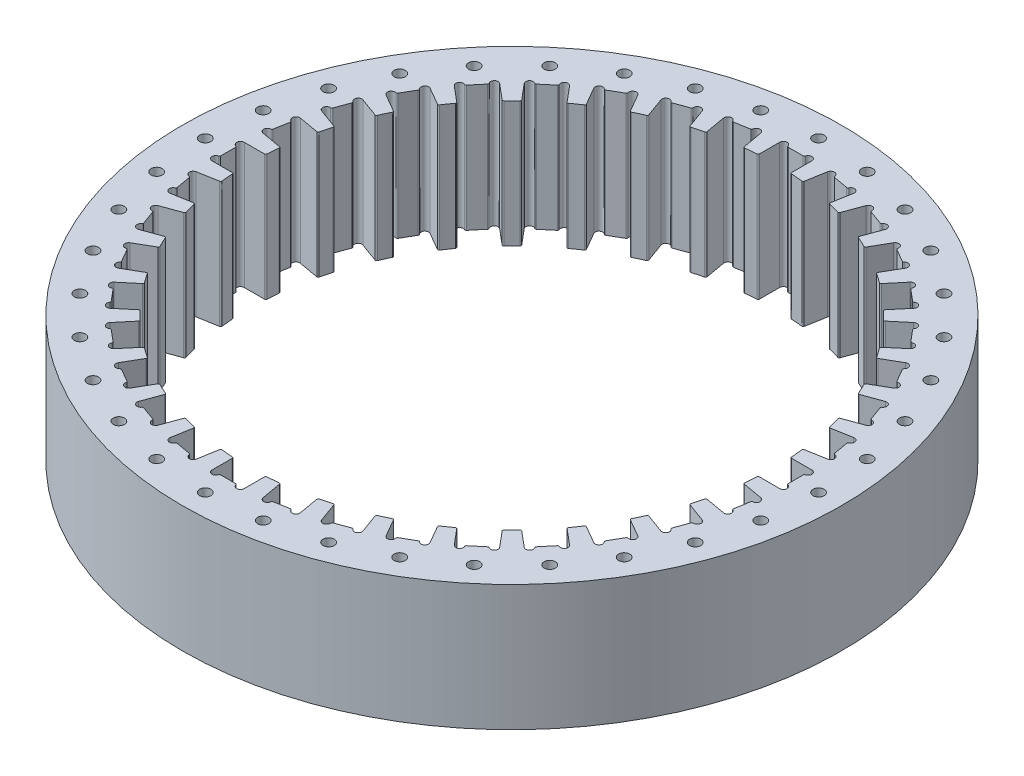
SolidWorks part; units mm, degrees
material "ABS"
ref_plane "Front Plane" through (0, 0, 0) normal (0, 0, 1) x (1, 0, 0)
ref_plane "Top Plane" through (0, 0, 0) normal (0, 1, 0) x (1, 0, 0)
ref_plane "Right Plane" through (0, 0, 0) normal (1, 0, 0) x (0, 0, -1)
sketch "Sketch1" plane through (0, 0, 0) normal (0, 1, 0) x (1, 0, 0)
  line L0 (12.4442, 51.8515) -> (13.1523, 55.8673)
  line L1 (11.433, 56.1704) -> (8.4679, 56.6933)
  line L2 (6.7487, 56.9964) -> (6.0406, 52.9807)
  line L3 (21.259, 48.9029) -> (22.6537, 52.7347)
  line L4 (21.0132, 53.3317) -> (18.1839, 54.3615)
  line L5 (16.5434, 54.9586) -> (15.1488, 51.1268)
  line L6 (29.428, 44.4683) -> (31.4668, 47.9997)
  line L7 (3.2512, 53.2247) -> (3.2512, 57.3024)
  line L8 (1.5055, 57.3024) -> (-1.5055, 57.3024)
  line L9 (-3.2512, 57.3024) -> (-3.2512, 53.2247)
  line L10 (29.955, 48.8726) -> (27.3474, 50.3781)
  line L11 (25.8356, 51.2509) -> (23.7967, 47.7195)
  line L12 (36.7027, 38.6827) -> (39.3238, 41.8064)
  line L13 (37.9865, 42.9285) -> (35.68, 44.8639)
  line L14 (34.3427, 45.986) -> (31.7216, 42.8623)
  line L15 (42.8623, 31.7216) -> (45.986, 34.3427)
  line L16 (44.8639, 35.68) -> (42.9285, 37.9865)
  line L17 (41.8064, 39.3238) -> (38.6827, 36.7027)
  line L18 (47.7195, 23.7967) -> (51.2509, 25.8356)
  line L19 (50.3781, 27.3474) -> (48.8726, 29.955)
  line L20 (47.9997, 31.4668) -> (44.4683, 29.428)
  line L21 (51.1268, 15.1488) -> (54.9586, 16.5434)
  line L22 (54.3615, 18.1839) -> (53.3317, 21.0132)
  line L23 (52.7347, 22.6537) -> (48.9029, 21.259)
  line L24 (52.9807, 6.0406) -> (56.9964, 6.7487)
  line L25 (56.6933, 8.4679) -> (56.1704, 11.433)
  line L26 (55.8673, 13.1523) -> (51.8515, 12.4442)
  line L27 (53.2247, -3.2512) -> (57.3024, -3.2512)
  line L28 (57.3024, -1.5055) -> (57.3024, 1.5055)
  line L29 (57.3024, 3.2512) -> (53.2247, 3.2512)
  line L30 (51.8515, -12.4442) -> (55.8673, -13.1523)
  line L31 (56.1704, -11.433) -> (56.6933, -8.4679)
  line L32 (56.9964, -6.7487) -> (52.9807, -6.0406)
  line L33 (48.9029, -21.259) -> (52.7347, -22.6537)
  line L34 (53.3317, -21.0132) -> (54.3615, -18.1839)
  line L35 (54.9586, -16.5434) -> (51.1268, -15.1488)
  line L36 (44.4683, -29.428) -> (47.9997, -31.4668)
  line L37 (48.8726, -29.955) -> (50.3781, -27.3474)
  line L38 (51.2509, -25.8356) -> (47.7195, -23.7967)
  line L39 (38.6827, -36.7027) -> (41.8064, -39.3238)
  line L40 (42.9285, -37.9865) -> (44.8639, -35.68)
  line L41 (45.986, -34.3427) -> (42.8623, -31.7216)
  line L42 (31.7216, -42.8623) -> (34.3427, -45.986)
  line L43 (35.68, -44.8639) -> (37.9865, -42.9285)
  line L44 (39.3238, -41.8064) -> (36.7027, -38.6827)
  line L45 (23.7967, -47.7195) -> (25.8356, -51.2509)
  line L46 (27.3474, -50.3781) -> (29.955, -48.8726)
  line L47 (31.4668, -47.9997) -> (29.428, -44.4683)
  line L48 (15.1488, -51.1268) -> (16.5434, -54.9586)
  line L49 (18.1839, -54.3615) -> (21.0132, -53.3317)
  line L50 (22.6537, -52.7347) -> (21.259, -48.9029)
  line L51 (6.0406, -52.9807) -> (6.7487, -56.9964)
  line L52 (8.4679, -56.6933) -> (11.433, -56.1704)
  line L53 (13.1523, -55.8673) -> (12.4442, -51.8515)
  line L54 (-3.2512, -53.2247) -> (-3.2512, -57.3024)
  line L55 (-1.5055, -57.3024) -> (1.5055, -57.3024)
  line L56 (3.2512, -57.3024) -> (3.2512, -53.2247)
  line L57 (-12.4442, -51.8515) -> (-13.1523, -55.8673)
  line L58 (-11.433, -56.1704) -> (-8.4679, -56.6933)
  line L59 (-6.7487, -56.9964) -> (-6.0406, -52.9807)
  line L60 (-21.259, -48.9029) -> (-22.6537, -52.7347)
  line L61 (-21.0132, -53.3317) -> (-18.1839, -54.3615)
  line L62 (-16.5434, -54.9586) -> (-15.1488, -51.1268)
  line L63 (-29.428, -44.4683) -> (-31.4668, -47.9997)
  line L64 (-29.955, -48.8726) -> (-27.3474, -50.3781)
  line L65 (-25.8356, -51.2509) -> (-23.7967, -47.7195)
  line L66 (-36.7027, -38.6827) -> (-39.3238, -41.8064)
  line L67 (-37.9865, -42.9285) -> (-35.68, -44.8639)
  line L68 (-34.3427, -45.986) -> (-31.7216, -42.8623)
  line L69 (-42.8623, -31.7216) -> (-45.986, -34.3427)
  line L70 (-44.8639, -35.68) -> (-42.9285, -37.9865)
  line L71 (-41.8064, -39.3238) -> (-38.6827, -36.7027)
  line L72 (-47.7195, -23.7967) -> (-51.2509, -25.8356)
  line L73 (-50.3781, -27.3474) -> (-48.8726, -29.955)
  line L74 (-47.9997, -31.4668) -> (-44.4683, -29.428)
  line L75 (-51.1268, -15.1488) -> (-54.9586, -16.5434)
  line L76 (-54.3615, -18.1839) -> (-53.3317, -21.0132)
  line L77 (-52.7347, -22.6537) -> (-48.9029, -21.259)
  line L78 (-52.9807, -6.0406) -> (-56.9964, -6.7487)
  line L79 (-56.6933, -8.4679) -> (-56.1704, -11.433)
  line L80 (-55.8673, -13.1523) -> (-51.8515, -12.4442)
  line L81 (-53.2247, 3.2512) -> (-57.3024, 3.2512)
  line L82 (-57.3024, 1.5055) -> (-57.3024, -1.5055)
  line L83 (-57.3024, -3.2512) -> (-53.2247, -3.2512)
  line L84 (-51.8515, 12.4442) -> (-55.8673, 13.1523)
  line L85 (-56.1704, 11.433) -> (-56.6933, 8.4679)
  line L86 (-56.9964, 6.7487) -> (-52.9807, 6.0406)
  line L87 (-48.9029, 21.259) -> (-52.7347, 22.6537)
  line L88 (-53.3317, 21.0132) -> (-54.3615, 18.1839)
  line L89 (-54.9586, 16.5434) -> (-51.1268, 15.1488)
  line L90 (-44.4683, 29.428) -> (-47.9997, 31.4668)
  line L91 (-48.8726, 29.955) -> (-50.3781, 27.3474)
  line L92 (-51.2509, 25.8356) -> (-47.7195, 23.7967)
  line L93 (-38.6827, 36.7027) -> (-41.8064, 39.3238)
  line L94 (-42.9285, 37.9865) -> (-44.8639, 35.68)
  line L95 (-45.986, 34.3427) -> (-42.8623, 31.7216)
  line L96 (-31.7216, 42.8623) -> (-34.3427, 45.986)
  line L97 (-35.68, 44.8639) -> (-37.9865, 42.9285)
  line L98 (-39.3238, 41.8064) -> (-36.7027, 38.6827)
  line L99 (-23.7967, 47.7195) -> (-25.8356, 51.2509)
  line L100 (-27.3474, 50.3781) -> (-29.955, 48.8726)
  line L101 (-31.4668, 47.9997) -> (-29.428, 44.4683)
  line L102 (-15.1488, 51.1268) -> (-16.5434, 54.9586)
  line L103 (-18.1839, 54.3615) -> (-21.0132, 53.3317)
  line L104 (-22.6537, 52.7347) -> (-21.259, 48.9029)
  line L105 (-6.0406, 52.9807) -> (-6.7487, 56.9964)
  line L106 (-8.4679, 56.6933) -> (-11.433, 56.1704)
  line L107 (-13.1523, 55.8673) -> (-12.4442, 51.8515)
  line L108 (0, 0) -> (50000, 0) construction
  line L109 (0, 0) -> (0, -50000) construction
  arc A0 (-3.4885, 52.9713) -> (-5.7629, 52.7723) centre (0, 0) ccw
  arc A1 (-1.5055, 57.3024) -> (-1.7514, 57.4929) centre (-1.5055, 57.5564) cw
  arc A2 (-1.7514, 57.4929) -> (-3.2512, 57.3024) centre (-2.4892, 57.3024) ccw
  arc A3 (1.7514, 57.4929) -> (3.2512, 57.3024) centre (2.4892, 57.3024) cw
  arc A4 (1.5055, 57.3024) -> (1.7514, 57.4929) centre (1.5055, 57.5564) ccw
  arc A5 (5.7629, 52.7723) -> (3.4885, 52.9713) centre (0, 0) ccw
  arc A6 (3.4885, 52.9713) -> (3.2512, 53.2247) centre (3.5052, 53.2247) cw
  arc A7 (-3.4885, 52.9713) -> (-3.2512, 53.2247) centre (-3.5052, 53.2247) ccw
  arc A8 (8.4679, 56.6933) -> (8.2587, 56.9236) centre (8.512, 56.9434) cw
  arc A9 (8.2587, 56.9236) -> (6.7487, 56.9964) centre (7.4991, 56.8641) ccw
  arc A10 (11.7083, 56.3153) -> (13.1523, 55.8673) centre (12.4018, 55.9996) cw
  arc A11 (11.433, 56.1704) -> (11.7083, 56.3153) centre (11.4772, 56.4206) ccw
  arc A12 (12.6339, 51.5607) -> (12.4442, 51.8515) centre (12.6943, 51.8074) cw
  arc A13 (5.7629, 52.7723) -> (6.0406, 52.9807) centre (5.7904, 53.0248) ccw
  arc A14 (14.8391, 50.9698) -> (12.6339, 51.5607) centre (0, 0) ccw
  arc A15 (18.1839, 54.3615) -> (18.018, 54.6247) centre (18.2708, 54.6002) cw
  arc A16 (18.018, 54.6247) -> (16.5434, 54.9586) centre (17.2595, 54.698) ccw
  arc A17 (21.3095, 53.4266) -> (22.6537, 52.7347) centre (21.9377, 52.9953) cw
  arc A18 (21.0132, 53.3317) -> (21.3095, 53.4266) centre (21.1001, 53.5704) ccw
  arc A19 (21.3954, 48.5836) -> (21.259, 48.9029) centre (21.4977, 48.816) cw
  arc A20 (14.8391, 50.9698) -> (15.1488, 51.1268) centre (14.9101, 51.2137) ccw
  arc A21 (23.4645, 47.6187) -> (21.3954, 48.5836) centre (0, 0) ccw
  arc A22 (27.3474, 50.3781) -> (27.2297, 50.666) centre (27.4744, 50.598) cw
  arc A23 (27.2297, 50.666) -> (25.8356, 51.2509) centre (26.4955, 50.8699) ccw
  arc A24 (30.2632, 48.9146) -> (31.4668, 47.9997) centre (30.8069, 48.3807) cw
  arc A25 (29.955, 48.8726) -> (30.2632, 48.9146) centre (30.082, 49.0926) ccw
  arc A26 (29.5068, 44.1302) -> (29.428, 44.4683) centre (29.6479, 44.3413) cw
  arc A27 (23.4645, 47.6187) -> (23.7967, 47.7195) centre (23.5768, 47.8465) ccw
  arc A28 (31.3769, 42.8207) -> (29.5068, 44.1302) centre (0, 0) ccw
  arc A29 (35.68, 44.8639) -> (35.6141, 45.1679) centre (35.8433, 45.0585) cw
  arc A30 (35.6141, 45.1679) -> (34.3427, 45.986) centre (34.9264, 45.4962) ccw
  arc A31 (38.2974, 42.9163) -> (39.3238, 41.8064) centre (38.7401, 42.2962) cw
  arc A32 (37.9865, 42.9285) -> (38.2974, 42.9163) centre (38.1498, 43.1231) ccw
  arc A33 (36.7216, 38.336) -> (36.7027, 38.6827) centre (36.8973, 38.5194) cw
  arc A34 (31.3769, 42.8207) -> (31.7216, 42.8623) centre (31.527, 43.0256) ccw
  arc A35 (38.336, 36.7216) -> (36.7216, 38.336) centre (0, 0) ccw
  arc A36 (42.9285, 37.9865) -> (42.9163, 38.2974) centre (43.1231, 38.1498) cw
  arc A37 (42.9163, 38.2974) -> (41.8064, 39.3238) centre (42.2962, 38.7401) ccw
  arc A38 (45.1679, 35.6141) -> (45.986, 34.3427) centre (45.4962, 34.9264) cw
  arc A39 (44.8639, 35.68) -> (45.1679, 35.6141) centre (45.0585, 35.8433) ccw
  arc A40 (42.8207, 31.3769) -> (42.8623, 31.7216) centre (43.0256, 31.527) cw
  arc A41 (38.336, 36.7216) -> (38.6827, 36.7027) centre (38.5194, 36.8973) ccw
  arc A42 (44.1302, 29.5068) -> (42.8207, 31.3769) centre (0, 0) ccw
  arc A43 (48.8726, 29.955) -> (48.9146, 30.2632) centre (49.0926, 30.082) cw
  arc A44 (48.9146, 30.2632) -> (47.9997, 31.4668) centre (48.3807, 30.8069) ccw
  arc A45 (50.666, 27.2297) -> (51.2509, 25.8356) centre (50.8699, 26.4955) cw
  arc A46 (50.3781, 27.3474) -> (50.666, 27.2297) centre (50.598, 27.4744) ccw
  arc A47 (47.6187, 23.4645) -> (47.7195, 23.7967) centre (47.8465, 23.5768) cw
  arc A48 (44.1302, 29.5068) -> (44.4683, 29.428) centre (44.3413, 29.6479) ccw
  arc A49 (48.5836, 21.3954) -> (47.6187, 23.4645) centre (0, 0) ccw
  arc A50 (53.3317, 21.0132) -> (53.4266, 21.3095) centre (53.5704, 21.1001) cw
  arc A51 (53.4266, 21.3095) -> (52.7347, 22.6537) centre (52.9953, 21.9377) ccw
  arc A52 (54.6247, 18.018) -> (54.9586, 16.5434) centre (54.698, 17.2595) cw
  arc A53 (54.3615, 18.1839) -> (54.6247, 18.018) centre (54.6002, 18.2708) ccw
  arc A54 (50.9698, 14.8391) -> (51.1268, 15.1488) centre (51.2137, 14.9101) cw
  arc A55 (48.5836, 21.3954) -> (48.9029, 21.259) centre (48.816, 21.4977) ccw
  arc A56 (51.5607, 12.6339) -> (50.9698, 14.8391) centre (0, 0) ccw
  arc A57 (56.1704, 11.433) -> (56.3153, 11.7083) centre (56.4206, 11.4772) cw
  arc A58 (56.3153, 11.7083) -> (55.8673, 13.1523) centre (55.9996, 12.4018) ccw
  arc A59 (56.9236, 8.2587) -> (56.9964, 6.7487) centre (56.8641, 7.4991) cw
  arc A60 (56.6933, 8.4679) -> (56.9236, 8.2587) centre (56.9434, 8.512) ccw
  arc A61 (52.7723, 5.7629) -> (52.9807, 6.0406) centre (53.0248, 5.7904) cw
  arc A62 (51.5607, 12.6339) -> (51.8515, 12.4442) centre (51.8074, 12.6943) ccw
  arc A63 (52.9713, 3.4885) -> (52.7723, 5.7629) centre (0, 0) ccw
  arc A64 (57.3024, 1.5055) -> (57.4929, 1.7514) centre (57.5564, 1.5055) cw
  arc A65 (57.4929, 1.7514) -> (57.3024, 3.2512) centre (57.3024, 2.4892) ccw
  arc A66 (57.4929, -1.7514) -> (57.3024, -3.2512) centre (57.3024, -2.4892) cw
  arc A67 (57.3024, -1.5055) -> (57.4929, -1.7514) centre (57.5564, -1.5055) ccw
  arc A68 (52.9713, -3.4885) -> (53.2247, -3.2512) centre (53.2247, -3.5052) cw
  arc A69 (52.9713, 3.4885) -> (53.2247, 3.2512) centre (53.2247, 3.5052) ccw
  arc A70 (52.7723, -5.7629) -> (52.9713, -3.4885) centre (0, 0) ccw
  arc A71 (56.6933, -8.4679) -> (56.9236, -8.2587) centre (56.9434, -8.512) cw
  arc A72 (56.9236, -8.2587) -> (56.9964, -6.7487) centre (56.8641, -7.4991) ccw
  arc A73 (56.3153, -11.7083) -> (55.8673, -13.1523) centre (55.9996, -12.4018) cw
  arc A74 (56.1704, -11.433) -> (56.3153, -11.7083) centre (56.4206, -11.4772) ccw
  arc A75 (51.5607, -12.6339) -> (51.8515, -12.4442) centre (51.8074, -12.6943) cw
  arc A76 (52.7723, -5.7629) -> (52.9807, -6.0406) centre (53.0248, -5.7904) ccw
  arc A77 (50.9698, -14.8391) -> (51.5607, -12.6339) centre (0, 0) ccw
  arc A78 (54.3615, -18.1839) -> (54.6247, -18.018) centre (54.6002, -18.2708) cw
  arc A79 (54.6247, -18.018) -> (54.9586, -16.5434) centre (54.698, -17.2595) ccw
  arc A80 (53.4266, -21.3095) -> (52.7347, -22.6537) centre (52.9953, -21.9377) cw
  arc A81 (53.3317, -21.0132) -> (53.4266, -21.3095) centre (53.5704, -21.1001) ccw
  arc A82 (48.5836, -21.3954) -> (48.9029, -21.259) centre (48.816, -21.4977) cw
  arc A83 (50.9698, -14.8391) -> (51.1268, -15.1488) centre (51.2137, -14.9101) ccw
  arc A84 (47.6187, -23.4645) -> (48.5836, -21.3954) centre (0, 0) ccw
  arc A85 (50.3781, -27.3474) -> (50.666, -27.2297) centre (50.598, -27.4744) cw
  arc A86 (50.666, -27.2297) -> (51.2509, -25.8356) centre (50.8699, -26.4955) ccw
  arc A87 (48.9146, -30.2632) -> (47.9997, -31.4668) centre (48.3807, -30.8069) cw
  arc A88 (48.8726, -29.955) -> (48.9146, -30.2632) centre (49.0926, -30.082) ccw
  arc A89 (44.1302, -29.5068) -> (44.4683, -29.428) centre (44.3413, -29.6479) cw
  arc A90 (47.6187, -23.4645) -> (47.7195, -23.7967) centre (47.8465, -23.5768) ccw
  arc A91 (42.8207, -31.3769) -> (44.1302, -29.5068) centre (0, 0) ccw
  arc A92 (44.8639, -35.68) -> (45.1679, -35.6141) centre (45.0585, -35.8433) cw
  arc A93 (45.1679, -35.6141) -> (45.986, -34.3427) centre (45.4962, -34.9264) ccw
  arc A94 (42.9163, -38.2974) -> (41.8064, -39.3238) centre (42.2962, -38.7401) cw
  arc A95 (42.9285, -37.9865) -> (42.9163, -38.2974) centre (43.1231, -38.1498) ccw
  arc A96 (38.336, -36.7216) -> (38.6827, -36.7027) centre (38.5194, -36.8973) cw
  arc A97 (42.8207, -31.3769) -> (42.8623, -31.7216) centre (43.0256, -31.527) ccw
  arc A98 (36.7216, -38.336) -> (38.336, -36.7216) centre (0, 0) ccw
  arc A99 (37.9865, -42.9285) -> (38.2974, -42.9163) centre (38.1498, -43.1231) cw
  arc A100 (38.2974, -42.9163) -> (39.3238, -41.8064) centre (38.7401, -42.2962) ccw
  arc A101 (35.6141, -45.1679) -> (34.3427, -45.986) centre (34.9264, -45.4962) cw
  arc A102 (35.68, -44.8639) -> (35.6141, -45.1679) centre (35.8433, -45.0585) ccw
  arc A103 (31.3769, -42.8207) -> (31.7216, -42.8623) centre (31.527, -43.0256) cw
  arc A104 (36.7216, -38.336) -> (36.7027, -38.6827) centre (36.8973, -38.5194) ccw
  arc A105 (29.5068, -44.1302) -> (31.3769, -42.8207) centre (0, 0) ccw
  arc A106 (29.955, -48.8726) -> (30.2632, -48.9146) centre (30.082, -49.0926) cw
  arc A107 (30.2632, -48.9146) -> (31.4668, -47.9997) centre (30.8069, -48.3807) ccw
  arc A108 (27.2297, -50.666) -> (25.8356, -51.2509) centre (26.4955, -50.8699) cw
  arc A109 (27.3474, -50.3781) -> (27.2297, -50.666) centre (27.4744, -50.598) ccw
  arc A110 (23.4645, -47.6187) -> (23.7967, -47.7195) centre (23.5768, -47.8465) cw
  arc A111 (29.5068, -44.1302) -> (29.428, -44.4683) centre (29.6479, -44.3413) ccw
  arc A112 (21.3954, -48.5836) -> (23.4645, -47.6187) centre (0, 0) ccw
  arc A113 (21.0132, -53.3317) -> (21.3095, -53.4266) centre (21.1001, -53.5704) cw
  arc A114 (21.3095, -53.4266) -> (22.6537, -52.7347) centre (21.9377, -52.9953) ccw
  arc A115 (18.018, -54.6247) -> (16.5434, -54.9586) centre (17.2595, -54.698) cw
  arc A116 (18.1839, -54.3615) -> (18.018, -54.6247) centre (18.2708, -54.6002) ccw
  arc A117 (14.8391, -50.9698) -> (15.1488, -51.1268) centre (14.9101, -51.2137) cw
  arc A118 (21.3954, -48.5836) -> (21.259, -48.9029) centre (21.4977, -48.816) ccw
  arc A119 (12.6339, -51.5607) -> (14.8391, -50.9698) centre (0, 0) ccw
  arc A120 (11.433, -56.1704) -> (11.7083, -56.3153) centre (11.4772, -56.4206) cw
  arc A121 (11.7083, -56.3153) -> (13.1523, -55.8673) centre (12.4018, -55.9996) ccw
  arc A122 (8.2587, -56.9236) -> (6.7487, -56.9964) centre (7.4991, -56.8641) cw
  arc A123 (8.4679, -56.6933) -> (8.2587, -56.9236) centre (8.512, -56.9434) ccw
  arc A124 (5.7629, -52.7723) -> (6.0406, -52.9807) centre (5.7904, -53.0248) cw
  arc A125 (12.6339, -51.5607) -> (12.4442, -51.8515) centre (12.6943, -51.8074) ccw
  arc A126 (3.4885, -52.9713) -> (5.7629, -52.7723) centre (0, 0) ccw
  arc A127 (1.5055, -57.3024) -> (1.7514, -57.4929) centre (1.5055, -57.5564) cw
  arc A128 (1.7514, -57.4929) -> (3.2512, -57.3024) centre (2.4892, -57.3024) ccw
  arc A129 (-1.7514, -57.4929) -> (-3.2512, -57.3024) centre (-2.4892, -57.3024) cw
  arc A130 (-1.5055, -57.3024) -> (-1.7514, -57.4929) centre (-1.5055, -57.5564) ccw
  arc A131 (-3.4885, -52.9713) -> (-3.2512, -53.2247) centre (-3.5052, -53.2247) cw
  arc A132 (3.4885, -52.9713) -> (3.2512, -53.2247) centre (3.5052, -53.2247) ccw
  arc A133 (-5.7629, -52.7723) -> (-3.4885, -52.9713) centre (0, 0) ccw
  arc A134 (-8.4679, -56.6933) -> (-8.2587, -56.9236) centre (-8.512, -56.9434) cw
  arc A135 (-8.2587, -56.9236) -> (-6.7487, -56.9964) centre (-7.4991, -56.8641) ccw
  arc A136 (-11.7083, -56.3153) -> (-13.1523, -55.8673) centre (-12.4018, -55.9996) cw
  arc A137 (-11.433, -56.1704) -> (-11.7083, -56.3153) centre (-11.4772, -56.4206) ccw
  arc A138 (-12.6339, -51.5607) -> (-12.4442, -51.8515) centre (-12.6943, -51.8074) cw
  arc A139 (-5.7629, -52.7723) -> (-6.0406, -52.9807) centre (-5.7904, -53.0248) ccw
  arc A140 (-14.8391, -50.9698) -> (-12.6339, -51.5607) centre (0, 0) ccw
  arc A141 (-18.1839, -54.3615) -> (-18.018, -54.6247) centre (-18.2708, -54.6002) cw
  arc A142 (-18.018, -54.6247) -> (-16.5434, -54.9586) centre (-17.2595, -54.698) ccw
  arc A143 (-21.3095, -53.4266) -> (-22.6537, -52.7347) centre (-21.9377, -52.9953) cw
  arc A144 (-21.0132, -53.3317) -> (-21.3095, -53.4266) centre (-21.1001, -53.5704) ccw
  arc A145 (-21.3954, -48.5836) -> (-21.259, -48.9029) centre (-21.4977, -48.816) cw
  arc A146 (-14.8391, -50.9698) -> (-15.1488, -51.1268) centre (-14.9101, -51.2137) ccw
  arc A147 (-23.4645, -47.6187) -> (-21.3954, -48.5836) centre (0, 0) ccw
  arc A148 (-27.3474, -50.3781) -> (-27.2297, -50.666) centre (-27.4744, -50.598) cw
  arc A149 (-27.2297, -50.666) -> (-25.8356, -51.2509) centre (-26.4955, -50.8699) ccw
  arc A150 (-30.2632, -48.9146) -> (-31.4668, -47.9997) centre (-30.8069, -48.3807) cw
  arc A151 (-29.955, -48.8726) -> (-30.2632, -48.9146) centre (-30.082, -49.0926) ccw
  arc A152 (-29.5068, -44.1302) -> (-29.428, -44.4683) centre (-29.6479, -44.3413) cw
  arc A153 (-23.4645, -47.6187) -> (-23.7967, -47.7195) centre (-23.5768, -47.8465) ccw
  arc A154 (-31.3769, -42.8207) -> (-29.5068, -44.1302) centre (0, 0) ccw
  arc A155 (-35.68, -44.8639) -> (-35.6141, -45.1679) centre (-35.8433, -45.0585) cw
  arc A156 (-35.6141, -45.1679) -> (-34.3427, -45.986) centre (-34.9264, -45.4962) ccw
  arc A157 (-38.2974, -42.9163) -> (-39.3238, -41.8064) centre (-38.7401, -42.2962) cw
  arc A158 (-37.9865, -42.9285) -> (-38.2974, -42.9163) centre (-38.1498, -43.1231) ccw
  arc A159 (-36.7216, -38.336) -> (-36.7027, -38.6827) centre (-36.8973, -38.5194) cw
  arc A160 (-31.3769, -42.8207) -> (-31.7216, -42.8623) centre (-31.527, -43.0256) ccw
  arc A161 (-38.336, -36.7216) -> (-36.7216, -38.336) centre (0, 0) ccw
  arc A162 (-42.9285, -37.9865) -> (-42.9163, -38.2974) centre (-43.1231, -38.1498) cw
  arc A163 (-42.9163, -38.2974) -> (-41.8064, -39.3238) centre (-42.2962, -38.7401) ccw
  arc A164 (-45.1679, -35.6141) -> (-45.986, -34.3427) centre (-45.4962, -34.9264) cw
  arc A165 (-44.8639, -35.68) -> (-45.1679, -35.6141) centre (-45.0585, -35.8433) ccw
  arc A166 (-42.8207, -31.3769) -> (-42.8623, -31.7216) centre (-43.0256, -31.527) cw
  arc A167 (-38.336, -36.7216) -> (-38.6827, -36.7027) centre (-38.5194, -36.8973) ccw
  arc A168 (-44.1302, -29.5068) -> (-42.8207, -31.3769) centre (0, 0) ccw
  arc A169 (-48.8726, -29.955) -> (-48.9146, -30.2632) centre (-49.0926, -30.082) cw
  arc A170 (-48.9146, -30.2632) -> (-47.9997, -31.4668) centre (-48.3807, -30.8069) ccw
  arc A171 (-50.666, -27.2297) -> (-51.2509, -25.8356) centre (-50.8699, -26.4955) cw
  arc A172 (-50.3781, -27.3474) -> (-50.666, -27.2297) centre (-50.598, -27.4744) ccw
  arc A173 (-47.6187, -23.4645) -> (-47.7195, -23.7967) centre (-47.8465, -23.5768) cw
  arc A174 (-44.1302, -29.5068) -> (-44.4683, -29.428) centre (-44.3413, -29.6479) ccw
  arc A175 (-48.5836, -21.3954) -> (-47.6187, -23.4645) centre (0, 0) ccw
  arc A176 (-53.3317, -21.0132) -> (-53.4266, -21.3095) centre (-53.5704, -21.1001) cw
  arc A177 (-53.4266, -21.3095) -> (-52.7347, -22.6537) centre (-52.9953, -21.9377) ccw
  arc A178 (-54.6247, -18.018) -> (-54.9586, -16.5434) centre (-54.698, -17.2595) cw
  arc A179 (-54.3615, -18.1839) -> (-54.6247, -18.018) centre (-54.6002, -18.2708) ccw
  arc A180 (-50.9698, -14.8391) -> (-51.1268, -15.1488) centre (-51.2137, -14.9101) cw
  arc A181 (-48.5836, -21.3954) -> (-48.9029, -21.259) centre (-48.816, -21.4977) ccw
  arc A182 (-51.5607, -12.6339) -> (-50.9698, -14.8391) centre (0, 0) ccw
  arc A183 (-56.1704, -11.433) -> (-56.3153, -11.7083) centre (-56.4206, -11.4772) cw
  arc A184 (-56.3153, -11.7083) -> (-55.8673, -13.1523) centre (-55.9996, -12.4018) ccw
  arc A185 (-56.9236, -8.2587) -> (-56.9964, -6.7487) centre (-56.8641, -7.4991) cw
  arc A186 (-56.6933, -8.4679) -> (-56.9236, -8.2587) centre (-56.9434, -8.512) ccw
  arc A187 (-52.7723, -5.7629) -> (-52.9807, -6.0406) centre (-53.0248, -5.7904) cw
  arc A188 (-51.5607, -12.6339) -> (-51.8515, -12.4442) centre (-51.8074, -12.6943) ccw
  arc A189 (-52.9713, -3.4885) -> (-52.7723, -5.7629) centre (0, 0) ccw
  arc A190 (-57.3024, -1.5055) -> (-57.4929, -1.7514) centre (-57.5564, -1.5055) cw
  arc A191 (-57.4929, -1.7514) -> (-57.3024, -3.2512) centre (-57.3024, -2.4892) ccw
  arc A192 (-57.4929, 1.7514) -> (-57.3024, 3.2512) centre (-57.3024, 2.4892) cw
  arc A193 (-57.3024, 1.5055) -> (-57.4929, 1.7514) centre (-57.5564, 1.5055) ccw
  arc A194 (-52.9713, 3.4885) -> (-53.2247, 3.2512) centre (-53.2247, 3.5052) cw
  arc A195 (-52.9713, -3.4885) -> (-53.2247, -3.2512) centre (-53.2247, -3.5052) ccw
  arc A196 (-52.7723, 5.7629) -> (-52.9713, 3.4885) centre (0, 0) ccw
  arc A197 (-56.6933, 8.4679) -> (-56.9236, 8.2587) centre (-56.9434, 8.512) cw
  arc A198 (-56.9236, 8.2587) -> (-56.9964, 6.7487) centre (-56.8641, 7.4991) ccw
  arc A199 (-56.3153, 11.7083) -> (-55.8673, 13.1523) centre (-55.9996, 12.4018) cw
  arc A200 (-56.1704, 11.433) -> (-56.3153, 11.7083) centre (-56.4206, 11.4772) ccw
  arc A201 (-51.5607, 12.6339) -> (-51.8515, 12.4442) centre (-51.8074, 12.6943) cw
  arc A202 (-52.7723, 5.7629) -> (-52.9807, 6.0406) centre (-53.0248, 5.7904) ccw
  arc A203 (-50.9698, 14.8391) -> (-51.5607, 12.6339) centre (0, 0) ccw
  arc A204 (-54.3615, 18.1839) -> (-54.6247, 18.018) centre (-54.6002, 18.2708) cw
  arc A205 (-54.6247, 18.018) -> (-54.9586, 16.5434) centre (-54.698, 17.2595) ccw
  arc A206 (-53.4266, 21.3095) -> (-52.7347, 22.6537) centre (-52.9953, 21.9377) cw
  arc A207 (-53.3317, 21.0132) -> (-53.4266, 21.3095) centre (-53.5704, 21.1001) ccw
  arc A208 (-48.5836, 21.3954) -> (-48.9029, 21.259) centre (-48.816, 21.4977) cw
  arc A209 (-50.9698, 14.8391) -> (-51.1268, 15.1488) centre (-51.2137, 14.9101) ccw
  arc A210 (-47.6187, 23.4645) -> (-48.5836, 21.3954) centre (0, 0) ccw
  arc A211 (-50.3781, 27.3474) -> (-50.666, 27.2297) centre (-50.598, 27.4744) cw
  arc A212 (-50.666, 27.2297) -> (-51.2509, 25.8356) centre (-50.8699, 26.4955) ccw
  arc A213 (-48.9146, 30.2632) -> (-47.9997, 31.4668) centre (-48.3807, 30.8069) cw
  arc A214 (-48.8726, 29.955) -> (-48.9146, 30.2632) centre (-49.0926, 30.082) ccw
  arc A215 (-44.1302, 29.5068) -> (-44.4683, 29.428) centre (-44.3413, 29.6479) cw
  arc A216 (-47.6187, 23.4645) -> (-47.7195, 23.7967) centre (-47.8465, 23.5768) ccw
  arc A217 (-42.8207, 31.3769) -> (-44.1302, 29.5068) centre (0, 0) ccw
  arc A218 (-44.8639, 35.68) -> (-45.1679, 35.6141) centre (-45.0585, 35.8433) cw
  arc A219 (-45.1679, 35.6141) -> (-45.986, 34.3427) centre (-45.4962, 34.9264) ccw
  arc A220 (-42.9163, 38.2974) -> (-41.8064, 39.3238) centre (-42.2962, 38.7401) cw
  arc A221 (-42.9285, 37.9865) -> (-42.9163, 38.2974) centre (-43.1231, 38.1498) ccw
  arc A222 (-38.336, 36.7216) -> (-38.6827, 36.7027) centre (-38.5194, 36.8973) cw
  arc A223 (-42.8207, 31.3769) -> (-42.8623, 31.7216) centre (-43.0256, 31.527) ccw
  arc A224 (-36.7216, 38.336) -> (-38.336, 36.7216) centre (0, 0) ccw
  arc A225 (-37.9865, 42.9285) -> (-38.2974, 42.9163) centre (-38.1498, 43.1231) cw
  arc A226 (-38.2974, 42.9163) -> (-39.3238, 41.8064) centre (-38.7401, 42.2962) ccw
  arc A227 (-35.6141, 45.1679) -> (-34.3427, 45.986) centre (-34.9264, 45.4962) cw
  arc A228 (-35.68, 44.8639) -> (-35.6141, 45.1679) centre (-35.8433, 45.0585) ccw
  arc A229 (-31.3769, 42.8207) -> (-31.7216, 42.8623) centre (-31.527, 43.0256) cw
  arc A230 (-36.7216, 38.336) -> (-36.7027, 38.6827) centre (-36.8973, 38.5194) ccw
  arc A231 (-29.5068, 44.1302) -> (-31.3769, 42.8207) centre (0, 0) ccw
  arc A232 (-29.955, 48.8726) -> (-30.2632, 48.9146) centre (-30.082, 49.0926) cw
  arc A233 (-30.2632, 48.9146) -> (-31.4668, 47.9997) centre (-30.8069, 48.3807) ccw
  arc A234 (-27.2297, 50.666) -> (-25.8356, 51.2509) centre (-26.4955, 50.8699) cw
  arc A235 (-27.3474, 50.3781) -> (-27.2297, 50.666) centre (-27.4744, 50.598) ccw
  arc A236 (-23.4645, 47.6187) -> (-23.7967, 47.7195) centre (-23.5768, 47.8465) cw
  arc A237 (-29.5068, 44.1302) -> (-29.428, 44.4683) centre (-29.6479, 44.3413) ccw
  arc A238 (-21.3954, 48.5836) -> (-23.4645, 47.6187) centre (0, 0) ccw
  arc A239 (-21.0132, 53.3317) -> (-21.3095, 53.4266) centre (-21.1001, 53.5704) cw
  arc A240 (-21.3095, 53.4266) -> (-22.6537, 52.7347) centre (-21.9377, 52.9953) ccw
  arc A241 (-18.018, 54.6247) -> (-16.5434, 54.9586) centre (-17.2595, 54.698) cw
  arc A242 (-18.1839, 54.3615) -> (-18.018, 54.6247) centre (-18.2708, 54.6002) ccw
  arc A243 (-14.8391, 50.9698) -> (-15.1488, 51.1268) centre (-14.9101, 51.2137) cw
  arc A244 (-21.3954, 48.5836) -> (-21.259, 48.9029) centre (-21.4977, 48.816) ccw
  arc A245 (-12.6339, 51.5607) -> (-14.8391, 50.9698) centre (0, 0) ccw
  arc A246 (-11.433, 56.1704) -> (-11.7083, 56.3153) centre (-11.4772, 56.4206) cw
  arc A247 (-11.7083, 56.3153) -> (-13.1523, 55.8673) centre (-12.4018, 55.9996) ccw
  arc A248 (-8.2587, 56.9236) -> (-6.7487, 56.9964) centre (-7.4991, 56.8641) cw
  arc A249 (-8.4679, 56.6933) -> (-8.2587, 56.9236) centre (-8.512, 56.9434) ccw
  arc A250 (-5.7629, 52.7723) -> (-6.0406, 52.9807) centre (-5.7904, 53.0248) cw
  arc A251 (-12.6339, 51.5607) -> (-12.4442, 51.8515) centre (-12.6943, 51.8074) ccw
  circle A252 centre (0, 0) radius 66.548
  circle A253 centre (30.9626, 53.6288) radius 1.1303
  circle A254 centre (21.1797, 58.1907) radius 1.1303
  circle A255 centre (39.8048, 47.4375) radius 1.1303
  circle A256 centre (47.4375, 39.8048) radius 1.1303
  circle A257 centre (53.6288, 30.9626) radius 1.1303
  circle A258 centre (58.1907, 21.1797) radius 1.1303
  circle A259 centre (60.9844, 10.7532) radius 1.1303
  circle A260 centre (61.9252, 0) radius 1.1303
  circle A261 centre (60.9844, -10.7532) radius 1.1303
  circle A262 centre (58.1907, -21.1797) radius 1.1303
  circle A263 centre (53.6288, -30.9626) radius 1.1303
  circle A264 centre (47.4375, -39.8048) radius 1.1303
  circle A265 centre (39.8048, -47.4375) radius 1.1303
  circle A266 centre (30.9626, -53.6288) radius 1.1303
  circle A267 centre (21.1797, -58.1907) radius 1.1303
  circle A268 centre (10.7532, -60.9844) radius 1.1303
  circle A269 centre (0, -61.9252) radius 1.1303
  circle A270 centre (-10.7532, -60.9844) radius 1.1303
  circle A271 centre (-21.1797, -58.1907) radius 1.1303
  circle A272 centre (-30.9626, -53.6288) radius 1.1303
  circle A273 centre (-39.8048, -47.4375) radius 1.1303
  circle A274 centre (-47.4375, -39.8048) radius 1.1303
  circle A275 centre (-53.6288, -30.9626) radius 1.1303
  circle A276 centre (-58.1907, -21.1797) radius 1.1303
  circle A277 centre (-60.9844, -10.7532) radius 1.1303
  circle A278 centre (-61.9252, 0) radius 1.1303
  circle A279 centre (-60.9844, 10.7532) radius 1.1303
  circle A280 centre (-58.1907, 21.1797) radius 1.1303
  circle A281 centre (-53.6288, 30.9626) radius 1.1303
  circle A282 centre (-47.4375, 39.8048) radius 1.1303
  circle A283 centre (-39.8048, 47.4375) radius 1.1303
  circle A284 centre (-30.9626, 53.6288) radius 1.1303
  circle A285 centre (-21.1797, 58.1907) radius 1.1303
  circle A286 centre (-10.7532, 60.9844) radius 1.1303
  circle A287 centre (0, 61.9252) radius 1.1303
  circle A288 centre (10.7532, 60.9844) radius 1.1303
  point P626 (0, 0)
  point P654 (0, 0)
  point P659 (-6.3946, -54.9885)
  point P662 (-3.2512, -55.2636)
  dimension "D1" = 36
  dimension "D2" = 36
  dimension "D3" = 53.086
  dimension "D4" = 6.5024
  dimension "D5" = 0.254
  dimension "D6" = 0.762
  dimension "D7" = 0.254
  dimension "D9" = 2.2606
  dimension "D8" = 61.9252
  dimension "D10" = 57.3024
extrude "Boss-Extrude2" add sketch "Sketch1" along normal blind 25.4
